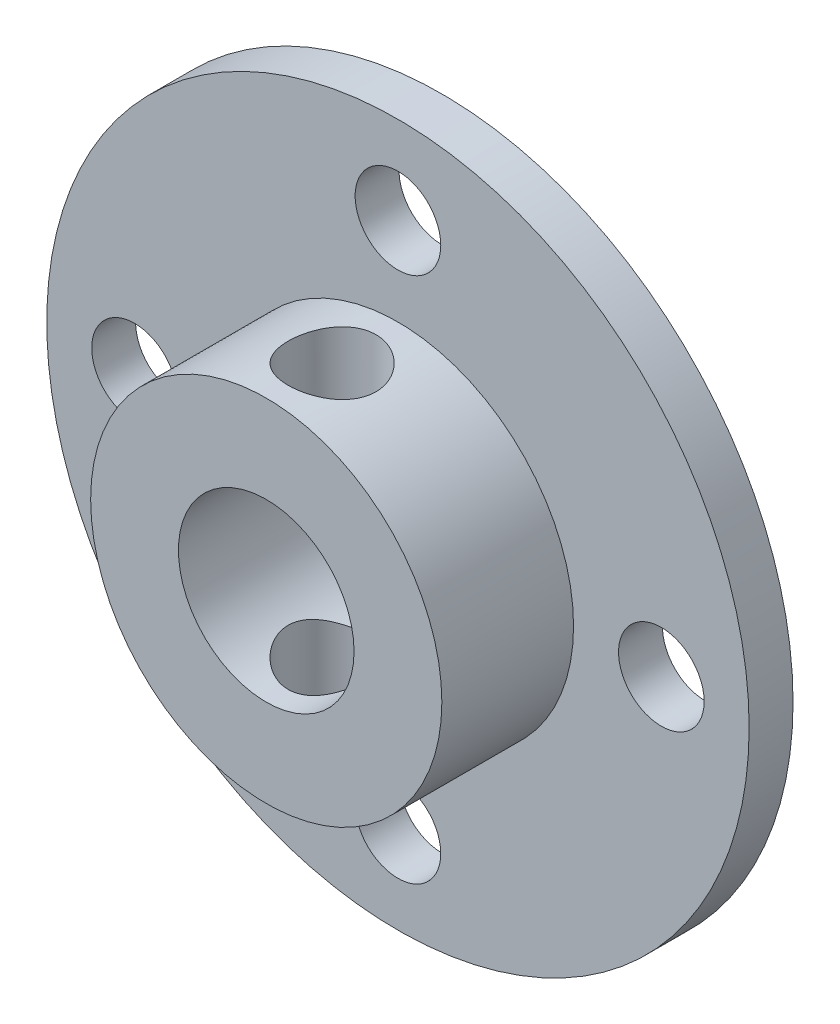
SolidWorks part; units mm, degrees
ref_plane "Front Plane" through (0, 0, 0) normal (0, 0, 1) x (1, 0, 0)
ref_plane "Top Plane" through (0, 0, 0) normal (0, 1, 0) x (1, 0, 0)
ref_plane "Right Plane" through (0, 0, 0) normal (1, 0, 0) x (0, 0, -1)
sketch "Sketch1" plane through (0, 0, 0) normal (0, 0, 1) x (1, 0, 0)
  circle A2 centre (0, 0) radius 8
  circle A3 centre (0, 0) radius 4
  dimension "D1" = 16
  dimension "D2" = 8
extrude "Boss-Extrude1" add sketch "Sketch1" along normal blind 8
sketch "Sketch2" plane through (0, 0, 0) normal (0, 0, 1) x (1, 0, 0)
  line L0 (8, 0) -> (16, 0) construction
  circle A0 centre (0, 0) radius 16
  circle A1 centre (12, 0) radius 1.95
  circle A2 centre (0, 0) radius 8 construction
  circle A3 centre (0, -12) radius 1.95
  circle A4 centre (-12, 0) radius 1.95
  circle A5 centre (0, 12) radius 1.95
  point P9 (12, 0)
  point P10 (-3.0837, 11.402)
  point P19 (0, 0)
  dimension "D1" = 32
  dimension "D2" = 3.9
  dimension "D3" = 4
extrude "Boss-Extrude2" add sketch "Sketch2" along normal blind 2
sketch "Sketch3" plane through (0, 0, 0) normal (0, 1, 0) x (1, 0, 0)
  line L0 (0, -2) -> (0, -8) construction
  line L1 (-8, -2) -> (8, -2) construction
  line L2 (-8, -8) -> (8, -8) construction
  circle A0 centre (0, -5) radius 2
  point P8 (0, -5)
  dimension "D1" = 4
extrude "Cut-Extrude1" cut sketch "Sketch3" against normal mid plane 20
